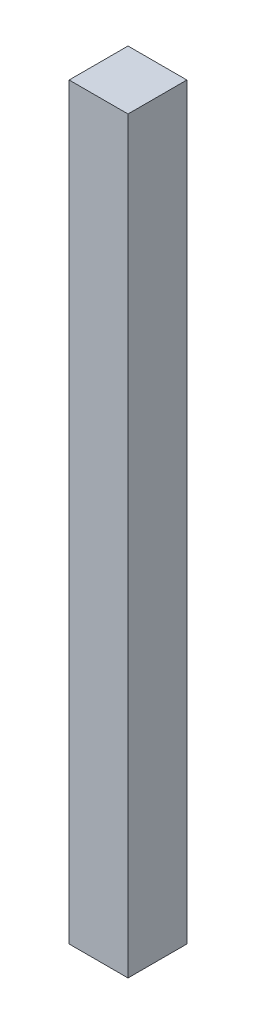
SolidWorks part; units mm, degrees
ref_plane "Front Plane" through (0, 0, 0) normal (0, 0, 1) x (1, 0, 0)
ref_plane "Top Plane" through (0, 0, 0) normal (0, 1, 0) x (1, 0, 0)
ref_plane "Right Plane" through (0, 0, 0) normal (1, 0, 0) x (0, 0, -1)
sketch "Sketch1" plane through (0, 0, 0) normal (0, 1, 0) x (1, 0, 0)
  line L1 (0, 0) -> (20, 0)
  line L2 (0, 0) -> (0, -20)
  line L3 (0, -20) -> (20, -20)
  line L4 (20, 0) -> (20, -20)
extrude "Boss-Extrude1" add sketch "Sketch1" along normal up to surface (254.2392 mm away)
